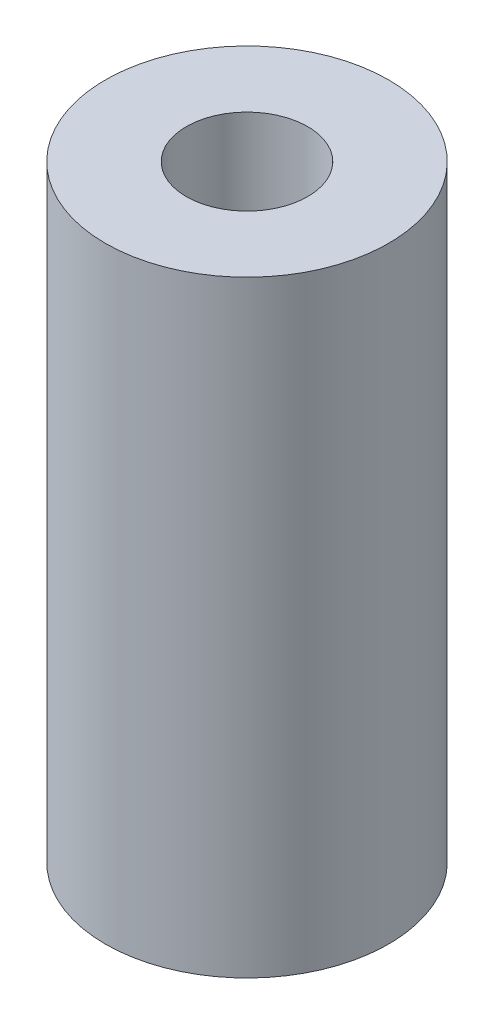
SolidWorks part; units mm, degrees
ref_plane "Front Plane" through (0, 0, 0) normal (0, 0, 1) x (1, 0, 0)
ref_plane "Top Plane" through (0, 0, 0) normal (0, 1, 0) x (1, 0, 0)
ref_plane "Right Plane" through (0, 0, 0) normal (1, 0, 0) x (0, 0, -1)
sketch "Sketch1" plane through (0, 0, 0) normal (0, 1, 0) x (1, 0, 0)
  circle A0 centre (0, 0) radius 1.5
  circle A1 centre (0, 0) radius 3.5
extrude "Boss-Extrude1" add sketch "Sketch1" along normal blind 15
